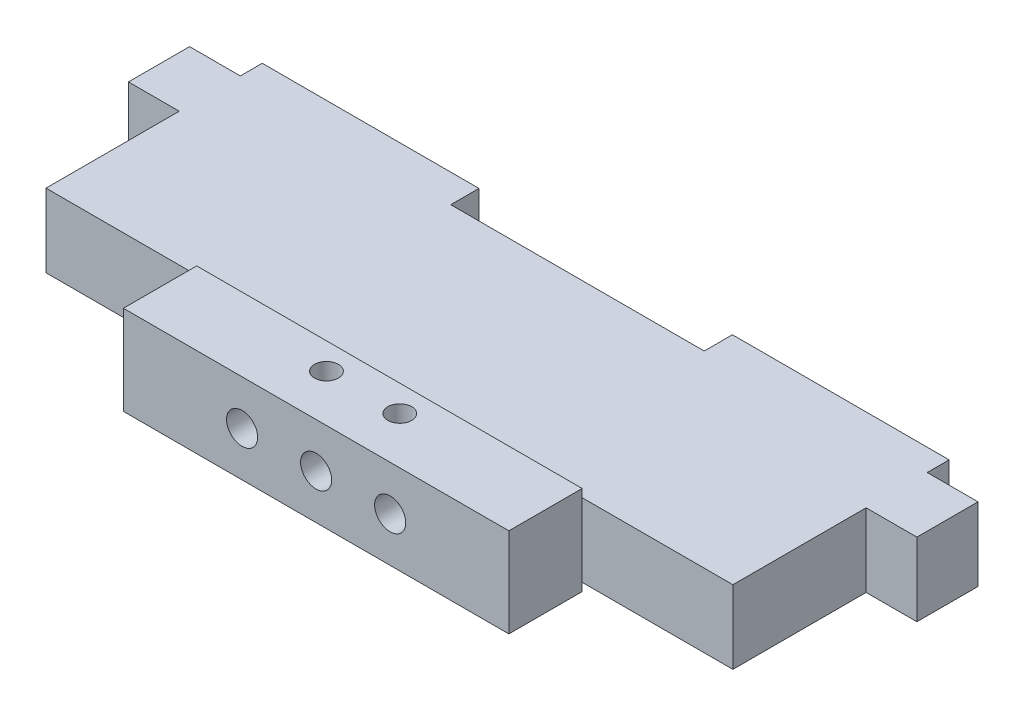
SolidWorks part; units mm, degrees
ref_plane "Front Plane" through (0, 0, 0) normal (0, 0, 1) x (1, 0, 0)
ref_plane "Top Plane" through (0, 0, 0) normal (0, 1, 0) x (1, 0, 0)
ref_plane "Right Plane" through (0, 0, 0) normal (1, 0, 0) x (0, 0, -1)
sketch "Sketch1" plane through (0, 0, 0) normal (0, 1, 0) x (1, 0, 0)
  line L0 (17.1196, 3.81) -> (46.3931, 3.81)
  line L1 (46.3931, 0.8509) -> (53.2511, 0.8509)
  line L2 (-46.3931, 3.81) -> (-17.1196, 3.81)
  line L3 (-46.3931, 3.81) -> (-46.3931, 0.8509)
  line L5 (46.3931, 3.81) -> (46.3931, 0.8509)
  line L7 (46.3931, -7.4041) -> (53.2511, -7.4041)
  line L8 (53.2511, 0.8509) -> (53.2511, -7.4041)
  line L9 (-46.3931, 0.8509) -> (-53.2511, 0.8509)
  line L11 (-46.3931, -7.4041) -> (-53.2511, -7.4041)
  line L12 (-53.2511, 0.8509) -> (-53.2511, -7.4041)
  line L14 (-17.1196, 3.81) -> (-17.1196, 0)
  line L15 (-17.1196, 0) -> (17.1196, 0)
  line L16 (17.1196, 3.81) -> (17.1196, 0)
  line L17 (-46.3931, -7.4041) -> (-46.3931, -25.4)
  line L18 (46.3931, -7.4041) -> (46.3931, -25.4)
  line L19 (-46.3931, -25.4) -> (-26.035, -25.4)
  line L21 (-26.035, -25.4) -> (-26.035, -35.306) construction
  line L22 (-26.035, -35.306) -> (26.035, -35.306) construction
  line L23 (26.035, -25.4) -> (26.035, -35.306) construction
  line L24 (-26.035, -25.4) -> (26.035, -25.4)
  line L25 (26.035, -25.4) -> (46.3931, -25.4)
  dimension "D1" = 92.7862
  dimension "D2" = 29.21
  dimension "D3" = 52.07
  dimension "D4" = 2.9591
  dimension "D5" = 8.255
  dimension "D6" = 25.4
  dimension "D7" = 9.906
  dimension "D8" = 6.858
  dimension "D10" = 34.2392
extrude "Boss-Extrude1" add sketch "Sketch1" along normal mid plane 9.906
sketch "Sketch4" plane through (0, 0, 0) normal (0, 1, 0) x (1, 0, 0)
  line L0 (-46.3931, -25.4) -> (46.3931, -25.4) construction
  line L1 (-26.035, -25.4) -> (26.035, -25.4)
  line L2 (-26.035, -25.4) -> (-26.035, -35.306)
  line L3 (-26.035, -35.306) -> (26.035, -35.306)
  line L4 (26.035, -25.4) -> (26.035, -35.306)
  line L5 (0, 0) -> (0, -35.306) construction
  line L6 (17.1196, 0) -> (-17.1196, 0) construction
  dimension "D1" = 9.906
  dimension "D2" = 52.07
extrude "Boss-Extrude3" add sketch "Sketch4" along normal mid plane 12.065
sketch "Sketch5" plane through (0, 6.0325, 0) normal (0, 1, 0) x (1, 0, 0)
  line L0 (-26.035, -35.306) -> (26.035, -35.306) construction
  line L1 (-4.953, -28.956) -> (-26.035, -28.956) construction
  line L2 (-26.035, -25.4) -> (-26.035, -35.306) construction
  line L3 (4.953, -28.956) -> (26.035, -28.956) construction
  line L4 (26.035, -35.306) -> (26.035, -25.4) construction
  circle A0 centre (-4.953, -28.956) radius 1.6129
  circle A1 centre (4.953, -28.956) radius 1.6129
  dimension "D1" = 3.2258
  dimension "D2" = 6.35
  dimension "D3" = 6.35
  dimension "D4" = 9.906
extrude "Cut-Extrude1" cut sketch "Sketch5" against normal blind 12.065
hole_wizard "M5x0.8 Tapped Hole1" positions "3DSketch1" profile "Sketch8" tap size "M5x0.8" standard "ANSI Metric"
sketch3d "3DSketch1"
  line L0 (5, 0, 0) -> (-5, 0, 0) construction
  line L1 (-10, 0, 35.306) -> (10, 0, 35.306) construction
  point P0 (0, 0, 35.306)
  point P2 (-5, 0, 0)
  point P4 (5, 0, 0)
  point P14 (-10, 0, 35.306)
  point P16 (10, 0, 35.306)
  dimension "D1" = 10
  dimension "D2" = 10
sketch "Sketch8" plane through (0, 0, 35.306) normal (1, 0, 0) x (0, -1, 0)
  line L0 (0, 0) -> (0, 8.8818)
  line L1 (0, 8.8818) -> (2.1, 7.62)
  line L2 (2.1, 7.62) -> (2.1, 0)
  line L5 (2.1, 0) -> (0, 0)
  line L10 (0, 8.8818) -> (-2.1, 7.62) construction
  line L11 (0, -6.35) -> (0, 107.95) construction
  dimension "Tap Drill Dia." = 4.2
  dimension "Tap Drill Depth" = 7.62
  dimension "Drill Angle" = 118
cosmetic thread "Hole Thread1"
cosmetic thread "Hole Thread2"
cosmetic thread "Hole Thread3"
cosmetic thread "Hole Thread4"
cosmetic thread "Hole Thread5"
